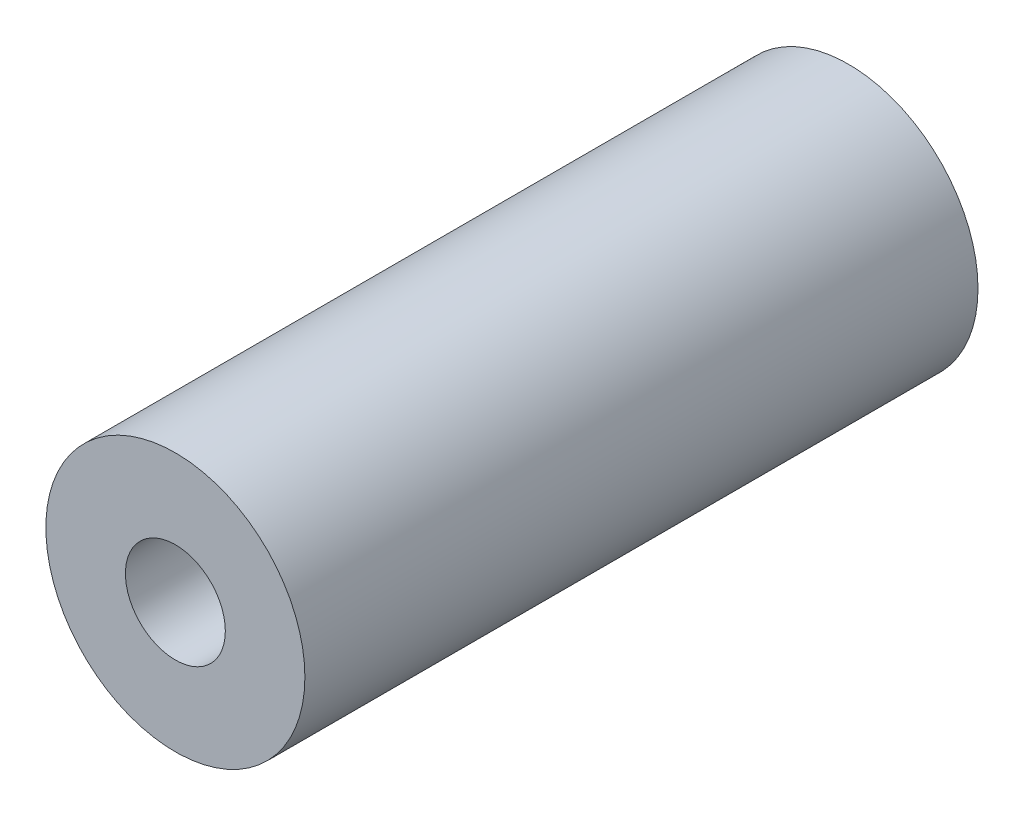
SolidWorks part; units mm, degrees
ref_plane "Front Plane" through (0, 0, 0) normal (0, 0, 1) x (1, 0, 0)
ref_plane "Top Plane" through (0, 0, 0) normal (0, 1, 0) x (1, 0, 0)
ref_plane "Right Plane" through (0, 0, 0) normal (1, 0, 0) x (0, 0, -1)
sketch "Sketch1" plane through (0, 0, 0) normal (0, 0, 1) x (1, 0, 0)
  circle A0 centre (0, 0) radius 3.5
  circle A1 centre (0, 0) radius 1.35
  dimension "D1" = 7
  dimension "D2" = 2.7
extrude "Boss-Extrude1" add sketch "Sketch1" against normal up to surface (18.188 mm away)
